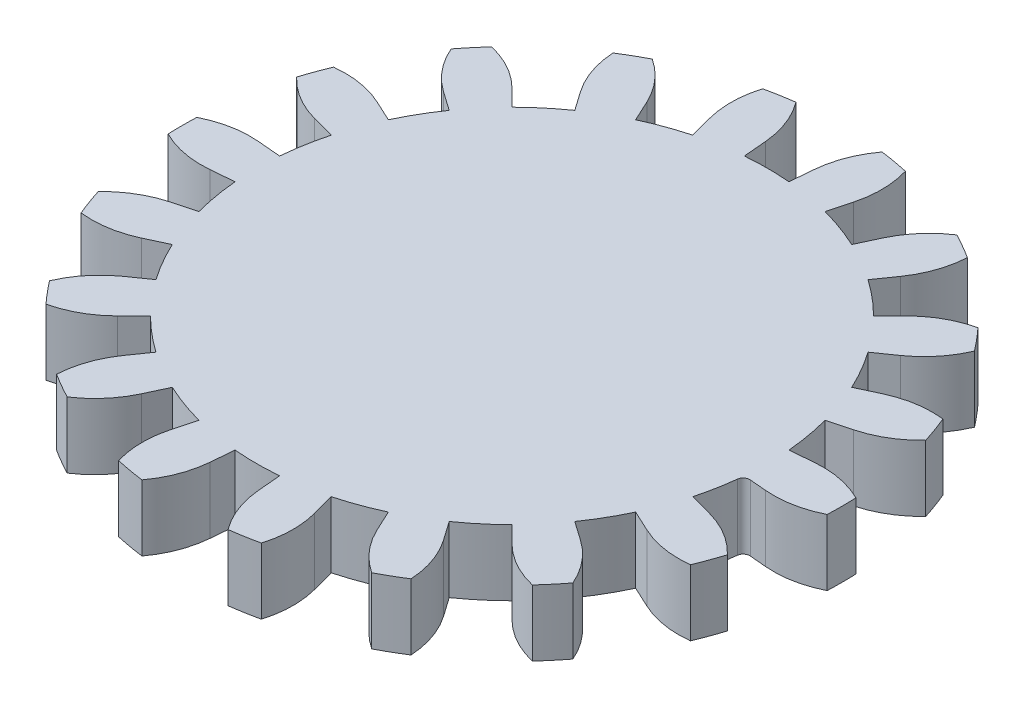
SolidWorks part; units mm, degrees
ref_plane "Front Plane" through (0, 0, 0) normal (0, 0, 1) x (1, 0, 0)
ref_plane "Top Plane" through (0, 0, 0) normal (0, 1, 0) x (1, 0, 0)
ref_plane "Right Plane" through (0, 0, 0) normal (1, 0, 0) x (0, 0, -1)
sketch "Sketch1" plane through (0, 0, 0) normal (0, 1, 0) x (1, 0, 0)
  line L0 (0, 0) -> (72.6697, 0) construction
  line L1 (0, 0) -> (38.1613, 6.7289) construction
  line L2 (0, 0) -> (61.2501, 5.3587) construction
  line L3 (0, 0) -> (61.2499, 2.6742) construction
  line L4 (42.1241, 3.6854) -> (38.6025, 3.3773)
  line L5 (0, 0) -> (38.1613, 6.7289)
  line L6 (42.1241, -3.6854) -> (38.6025, -3.3773)
  line L7 (0, 0) -> (38.1613, -6.7289)
  circle A0 centre (0, 0) radius 50 construction
  circle A1 centre (0, 0) radius 42.285 construction
  circle A2 centre (0, 0) radius 38.75 construction
  arc A3 (42.1241, 3.6854) -> (49.9488, 2.1808) centre (43.3928, -10.8157) cw
  arc A4 (38.6025, 3.3773) -> (38.1613, 6.7289) centre (0, 0) ccw
  arc A5 (49.9488, 2.1808) -> (49.9488, -2.1808) centre (0, 0) cw
  arc A6 (42.1241, -3.6854) -> (49.9488, -2.1808) centre (43.3928, 10.8157) ccw
  arc A7 (38.6025, -3.3773) -> (38.1613, -6.7289) centre (0, 0) cw
  dimension "D1" = 100
  dimension "D2" = 84.57
  dimension "D3" = 11.25
  dimension "D7" = 14.5564
  dimension "D4" = 10
  dimension "D5" = 5
  dimension "D6" = 2.5
extrude "Boss-Extrude1" add sketch "Sketch1" along normal blind 10 contours A7 L6 A6 A5 A3 L4 A4 L5 L7
fillet "Fillet4" radius 1 1 edges at (38.6025, 5, 3.3773)
pattern_circular "CirPattern1" count 18 over 360 about axis through (0, 0, 0) along (0, 1, 0) of "Boss-Extrude1"
sketch "Sketch3" plane through (0, 10, 0) normal (0, 1, 0) x (1, 0, 0)
  circle A0 centre (0, 0) radius 26.025
  circle A1 centre (0, 0) radius 14.9899
  dimension "D1" = 29.9797
  dimension "D2" = 52.0501
sketch "Sketch8" plane through (0, 10, 0) normal (0, 1, 0) x (1, 0, 0)
sketch "Sketch10" plane through (0, 10, 0) normal (0, 1, 0) x (1, 0, 0)
